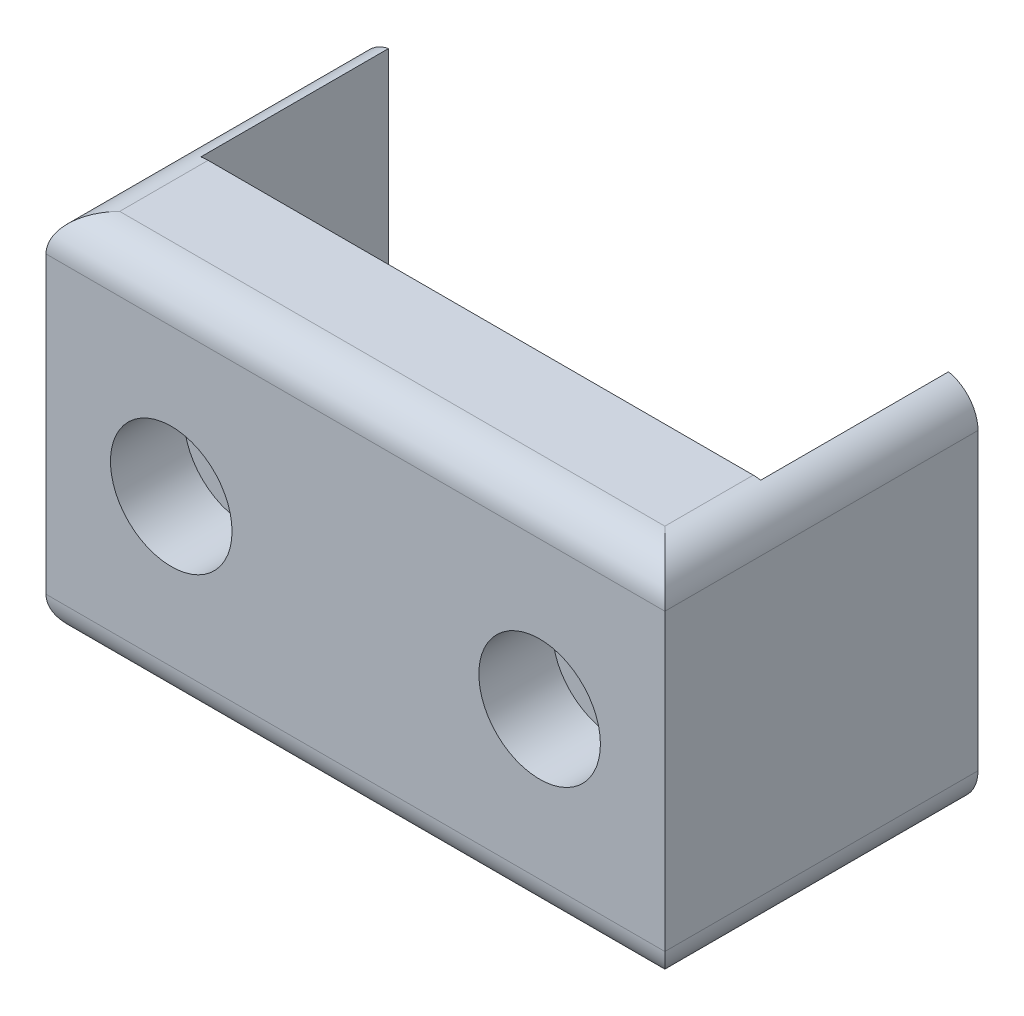
SolidWorks part; units mm, degrees
ref_plane "Front Plane" through (0, 0, 0) normal (0, 0, 1) x (1, 0, 0)
ref_plane "Top Plane" through (0, 0, 0) normal (0, 1, 0) x (1, 0, 0)
ref_plane "Right Plane" through (0, 0, 0) normal (1, 0, 0) x (0, 0, -1)
sketch "Sketch1" plane through (0, 0, 0) normal (0, 1, 0) x (1, 0, 0)
  line L0 (-21.336, 0) -> (21.336, 0)
  line L1 (-19.304, 12.954) -> (19.304, 12.954)
  line L2 (-19.304, 12.954) -> (-19.304, -12.954)
  line L3 (-19.304, -12.954) -> (19.304, -12.954)
  line L4 (19.304, 12.954) -> (19.304, -12.954)
  line L5 (-19.304, 12.954) -> (19.304, -12.954) construction
  line L6 (-19.304, -12.954) -> (19.304, 12.954) construction
  line L7 (-21.336, 21.59) -> (21.336, 21.59)
  line L8 (-21.336, 21.59) -> (-21.336, -21.59)
  line L9 (-21.336, -21.59) -> (21.336, -21.59)
  line L10 (21.336, 21.59) -> (21.336, -21.59)
  line L11 (-21.336, 21.59) -> (21.336, -21.59) construction
  line L12 (-21.336, -21.59) -> (21.336, 21.59) construction
  point P0 (0, 0)
  point P6 (0, 0)
  dimension "D1" = 38.608
  dimension "D2" = 25.908
  dimension "D3" = 42.672
  dimension "D4" = 43.18
extrude "Boss-Extrude1" add sketch "Sketch1" along normal blind 25.4 contours L10 L0 L4 L3 L2 L8 L9
sketch "Sketch2" plane through (0, 0, 21.59) normal (0, 0, 1) x (1, 0, 0)
  line L0 (-21.336, 12.7) -> (21.336, 12.7) construction
  line L1 (-21.336, 25.4) -> (-21.336, 0) construction
  line L2 (21.336, 25.4) -> (21.336, 0) construction
  line L3 (-21.336, 0) -> (21.336, 0) construction
  circle A0 centre (-12.7, 12.7) radius 2.54
  circle A1 centre (12.7, 12.7) radius 2.54
  point P15 (0, 0)
  dimension "D1" = 5.08
  dimension "D2" = 5.08
  dimension "D3" = 12.7
  dimension "D4" = 12.7
extrude "Cut-Extrude1" cut sketch "Sketch2" against normal through all
sketch "Sketch3" plane through (0, 0, 21.59) normal (0, 0, 1) x (1, 0, 0)
  circle A0 centre (-12.7, 12.7) radius 4.191
  circle A1 centre (12.7, 12.7) radius 4.191
  circle A2 centre (-12.7, 12.7) radius 2.54 construction
  circle A3 centre (12.7, 12.7) radius 2.54 construction
  dimension "D1" = 8.382
  dimension "D2" = 8.382
extrude "Cut-Extrude2" cut sketch "Sketch3" against normal blind 5.08
fillet "Fillet1" radius 2.54 3 edges at (-21.336, 25.4, 10.795) (21.336, 25.4, 10.795) (0, 25.4, 21.59)
fillet "Fillet2" radius 2.54 3 edges at (-21.336, 0, 10.795) (0, 0, 21.59) (21.336, 0, 10.795)
